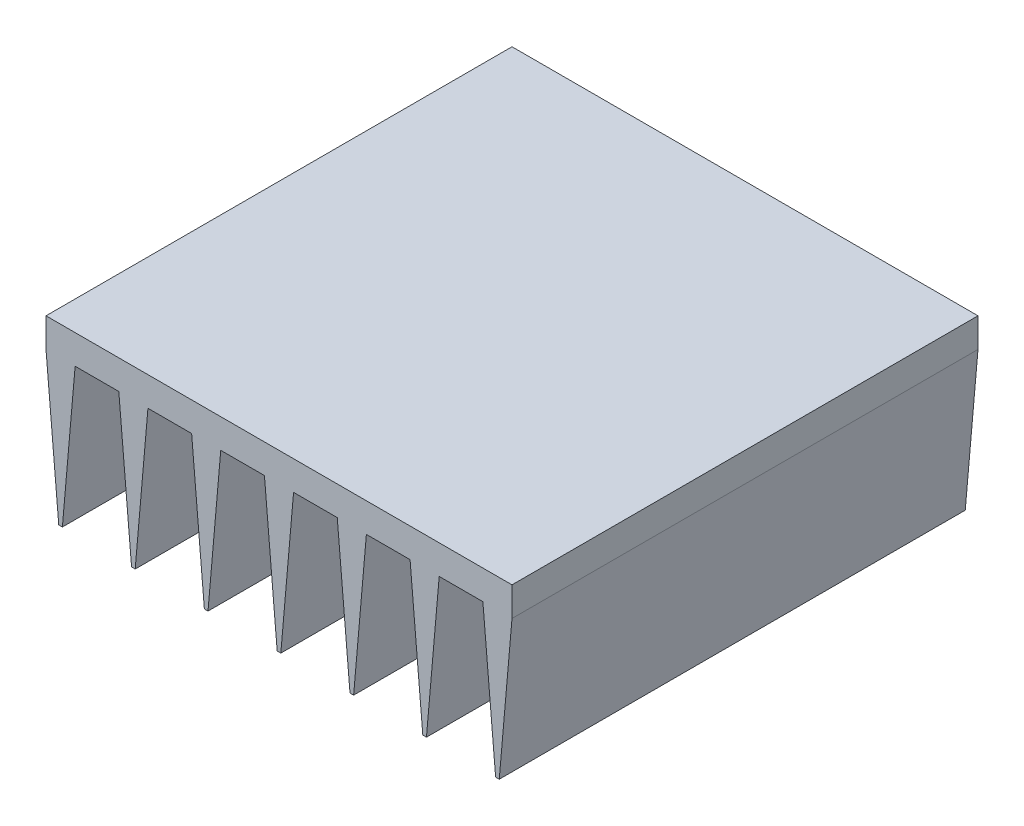
SolidWorks part; units mm, degrees
material "1060 Alloy"
ref_plane "Front Plane" through (0, 0, 0) normal (0, 0, 1) x (1, 0, 0)
ref_plane "Top Plane" through (0, 0, 0) normal (0, 1, 0) x (1, 0, 0)
ref_plane "Right Plane" through (0, 0, 0) normal (1, 0, 0) x (0, 0, -1)
sketch "Sketch1" plane through (0, 0, 0) normal (0, 1, 0) x (1, 0, 0)
  line L0 (-25.4, 25.4) -> (25.4, 25.4)
  line L1 (-25.4, 25.4) -> (-25.4, -25.4)
  line L2 (25.4, 25.4) -> (25.4, -25.4)
  line L3 (-25.4, -25.4) -> (25.4, -25.4)
  line L4 (-25.4, 25.4) -> (25.4, -25.4) construction
  line L5 (25.4, 25.4) -> (-25.4, -25.4) construction
  point P1 (0, 0)
  dimension "D1" = 50.8
  dimension "D2" = 50.8
extrude "Boss-Extrude1" add sketch "Sketch1" against normal blind 3.175
sketch "Sketch2" plane through (0, 0, 25.4) normal (0, 0, 1) x (1, 0, 0)
  line L0 (-25.4, -3.175) -> (-24.0106, -19.05)
  line L1 (-24.0106, -19.05) -> (-23.6144, -19.05)
  line L2 (-23.6144, -19.05) -> (-22.225, -3.175)
  line L3 (-25.4, -3.175) -> (25.4, -3.175) construction
  line L4 (-22.225, -3.175) -> (-25.4, -3.175)
  line L5 (-23.8125, -3.175) -> (-23.8125, -19.05) construction
  point P9 (0, 0)
  point P10 (-23.8125, -19.05)
  dimension "D1" = 0.3962
  dimension "D2" = 3.175
  dimension "D3" = 15.875
extrude "Boss-Extrude2" add sketch "Sketch2" against normal through all
pattern_linear "LPattern1" count 7 spacing 7.9375 along (1, 0, 0) of "Boss-Extrude2"
